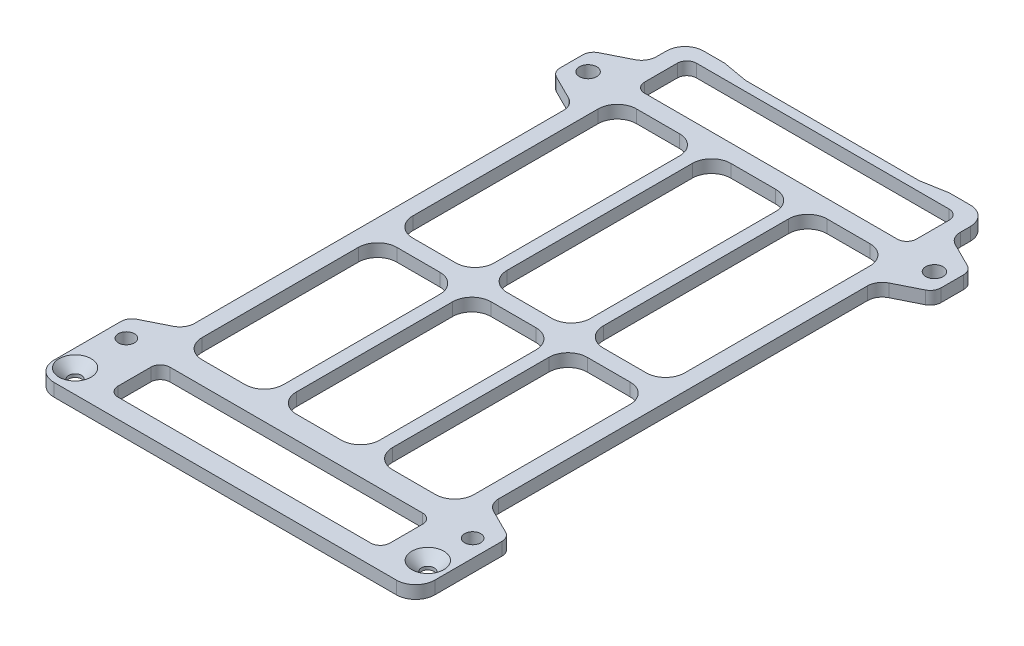
SolidWorks part; units mm, degrees
material "碳板"
ref_plane "前视基准面" through (0, 0, 0) normal (0, 0, 1) x (1, 0, 0)
ref_plane "上视基准面" through (0, 0, 0) normal (0, 1, 0) x (1, 0, 0)
ref_plane "右视基准面" through (0, 0, 0) normal (1, 0, 0) x (0, 0, -1)
sketch "草图1" plane through (0, 0, 0) normal (0, 1, 0) x (1, 0, 0)
  line L0 (-30, 43) -> (-30, -42) construction
  line L1 (-27, 40) -> (27, 40) construction
  line L2 (-27, 40) -> (-27, -40) construction
  line L3 (-27, -40) -> (27, -40) construction
  line L4 (27, 40) -> (27, -40) construction
  line L5 (-27, 40) -> (27, -40) construction
  line L6 (-27, -40) -> (27, 40) construction
  line L7 (-30, -42) -> (30, -42) construction
  line L8 (30, -42) -> (30, 43) construction
  line L9 (30, 43) -> (-30, 43) construction
  line L58 (-29.7, -30.1367) -> (-29.7, -43.6006)
  line L60 (29.7, -30.1367) -> (29.7, -43.6006)
  line L63 (-29.7, -43.6006) -> (29.7, -43.6006)
  line L106 (23.7, 47.3354) -> (23.7, 48.8994)
  line L107 (28.7603, 43.3838) -> (24.9714, 45.2782)
  line L108 (29.7, 38.3354) -> (29.7, 41.8633)
  line L109 (24.9714, 34.9205) -> (28.7603, 36.8149)
  line L110 (23.7, -24.6646) -> (23.7, 32.8633)
  line L111 (28.7603, -28.6162) -> (24.9714, -26.7218)
  line L119 (-24.9714, -26.7218) -> (-28.7603, -28.6162)
  line L120 (-23.7, 32.8633) -> (-23.7, -24.6646)
  line L121 (-28.7603, 36.8149) -> (-24.9714, 34.9205)
  line L122 (-29.7, 41.8633) -> (-29.7, 38.3354)
  line L123 (-24.9714, 45.2782) -> (-28.7603, 43.3838)
  line L124 (-23.7, 48.8994) -> (-23.7, 47.3354)
  line L125 (-17.5261, 51.7994) -> (-20.8, 51.7994)
  line L126 (-13.5261, 51.0994) -> (-17.5261, 51.7994)
  line L127 (13.5261, 51.0994) -> (-13.5261, 51.0994)
  line L128 (17.5261, 51.7994) -> (13.5261, 51.0994)
  line L129 (20.8, 51.7994) -> (17.5261, 51.7994)
  circle A0 centre (-27, 40) radius 1.35
  circle A1 centre (27, 40) radius 1.35
  circle A2 centre (-27, -40) radius 1
  circle A4 centre (26.5, -38.5) radius 1
  arc A85 (23.7, 48.8994) -> (20.8, 51.7994) centre (20.8, 48.8994) ccw
  arc A86 (23.7, 47.3354) -> (24.9714, 45.2782) centre (26, 47.3354) ccw
  arc A87 (29.7, 41.8633) -> (28.7603, 43.3838) centre (28, 41.8633) ccw
  arc A88 (28.7603, 36.8149) -> (29.7, 38.3354) centre (28, 38.3354) ccw
  arc A89 (24.9714, 34.9205) -> (23.7, 32.8633) centre (26, 32.8633) ccw
  arc A90 (23.7, -24.6646) -> (24.9714, -26.7218) centre (26, -24.6646) ccw
  arc A91 (29.7, -30.1367) -> (28.7603, -28.6162) centre (28, -30.1367) ccw
  arc A98 (-28.7603, -28.6162) -> (-29.7, -30.1367) centre (-28, -30.1367) ccw
  arc A99 (-24.9714, -26.7218) -> (-23.7, -24.6646) centre (-26, -24.6646) ccw
  arc A100 (-23.7, 32.8633) -> (-24.9714, 34.9205) centre (-26, 32.8633) ccw
  arc A101 (-29.7, 38.3354) -> (-28.7603, 36.8149) centre (-28, 38.3354) ccw
  arc A102 (-28.7603, 43.3838) -> (-29.7, 41.8633) centre (-28, 41.8633) ccw
  arc A103 (-24.9714, 45.2782) -> (-23.7, 47.3354) centre (-26, 47.3354) ccw
  arc A104 (-20.8, 51.7994) -> (-23.7, 48.8994) centre (-20.8, 48.8994) ccw
  circle A105 centre (-27, -32) radius 1.25
  circle A106 centre (27, -32) radius 1.25
  point P0 (0, 0)
  dimension "D1" = 2.7
  dimension "D2" = 2
  dimension "D5" = 1.5
  dimension "D6" = 53.5
  dimension "D11" = 2.5
  dimension "D13" = 72
  dimension "D3" = 80
  dimension "D4" = 54
  dimension "D7" = 3
  dimension "D8" = 3
  dimension "D9" = 2
  dimension "D12" = 3
other "对齐组1"
extrude "凸台-拉伸1" add sketch "草图1" along normal blind 2
fillet "圆角1" radius 3 2 edges at (29.7, 1, 43.6006) (-29.7, 1, 43.6006)
sketch "草图3" plane through (0, 2, 0) normal (0, 1, 0) x (1, 0, 0)
  line L4 (0, 51.0994) -> (0, -43.6006) construction
  line L5 (21.2, -29) -> (8.5, -29)
  line L6 (-6.5, 1.3653) -> (6.5, 1.3653)
  line L7 (-21.2, 38.75) -> (-8.5, 38.75)
  line L8 (-6.5, 1.3653) -> (-6.5, -29)
  line L29 (-26.7, -43.6006) -> (26.7, -43.6006) construction
  line L30 (-21.2, 38.75) -> (-21.2, 3.8653)
  line L31 (-21.2, 3.8653) -> (-8.5, 3.8653)
  line L32 (-8.5, 38.75) -> (-8.5, 3.8653)
  line L33 (13.5261, 51.0994) -> (-13.5261, 51.0994) construction
  line L35 (-23.7, 32.8633) -> (-23.7, -24.6646) construction
  line L36 (-27, 40) -> (27, 40) construction
  line L37 (-27, -32) -> (27, -32) construction
  line L38 (-6.5, 38.75) -> (6.5, 38.75)
  line L39 (-6.5, 38.75) -> (-6.5, 3.8653)
  line L40 (-6.5, 3.8653) -> (6.5, 3.8653)
  line L41 (6.5, 38.75) -> (6.5, 3.8653)
  line L42 (-21.2, 1.3653) -> (-8.5, 1.3653)
  line L43 (-21.2, 1.3653) -> (-21.2, -29)
  line L44 (-21.2, -29) -> (-8.5, -29)
  line L45 (-8.5, 1.3653) -> (-8.5, -29)
  line L46 (-6.5, -29) -> (6.5, -29)
  line L47 (6.5, 1.3653) -> (6.5, -29)
  line L48 (8.5, 1.3653) -> (8.5, -29)
  line L49 (21.2, 1.3653) -> (8.5, 1.3653)
  line L50 (21.2, 1.3653) -> (21.2, -29)
  line L51 (21.2, 3.8653) -> (8.5, 3.8653)
  line L52 (8.5, 38.75) -> (8.5, 3.8653)
  line L53 (21.2, 38.75) -> (8.5, 38.75)
  line L54 (21.2, 38.75) -> (21.2, 3.8653)
  line L55 (-21.2, -32.5) -> (21.2, -32.5)
  line L56 (-21.2, 49.5994) -> (21.2, 49.5994)
  line L57 (-21.2, 49.5994) -> (-21.2, 41.5)
  line L58 (-21.2, 41.5) -> (21.2, 41.5)
  line L59 (21.2, 49.5994) -> (21.2, 41.5)
  line L60 (-21.2, -32.5) -> (-21.2, -40.6006)
  line L61 (-21.2, -40.6006) -> (21.2, -40.6006)
  line L62 (21.2, -32.5) -> (21.2, -40.6006)
  point P20 (0, 38.75)
  dimension "D1" = 2.5
  dimension "D2" = 2.5
  dimension "D3" = 34.8847
  dimension "D4" = 2
  dimension "D5" = 2.5
  dimension "D6" = 3
  dimension "D7" = 1.5
  dimension "D9" = 3.5
  dimension "D8" = 1.5
  dimension "D10" = 3
  dimension "D11" = 13
extrude "切除-拉伸1" cut sketch "草图3" against normal through all
fillet "圆角2" radius 3 24 edges at (-8.5, 1, -38.75) (-8.5, 1, -3.8653) (-21.2, 1, -3.8653) (-21.2, 1, -38.75) (8.5, 1, -3.8653) (8.5, 1, -38.75) (21.2, 1, -3.8653) (6.5, 1, -38.75) (6.5, 1, -3.8653) (-6.5, 1, -3.8653) (-6.5, 1, -38.75) (6.5, 1, -1.3653) (6.5, 1, 29) (-6.5, 1, 29) (-6.5, 1, -1.3653) (-8.5, 1, -1.3653) (-8.5, 1, 29) (-21.2, 1, 29) (-21.2, 1, -1.3653) (8.5, 1, 29) (8.5, 1, -1.3653) (21.2, 1, -1.3653) (21.2, 1, 29) (21.2, 1, -38.75)
fillet "圆角3" radius 1.5 8 edges at (21.2, 1, -49.5994) (21.2, 1, -41.5) (-21.2, 1, -49.5994) (-21.2, 1, -41.5) (21.2, 1, 32.5) (21.2, 1, 40.6006) (-21.2, 1, 32.5) (-21.2, 1, 40.6006)
chamfer "倒角1" distance 1.5 angle 45 2 edges at (26.5, 2, 39.5) (-27, 2, 41)
